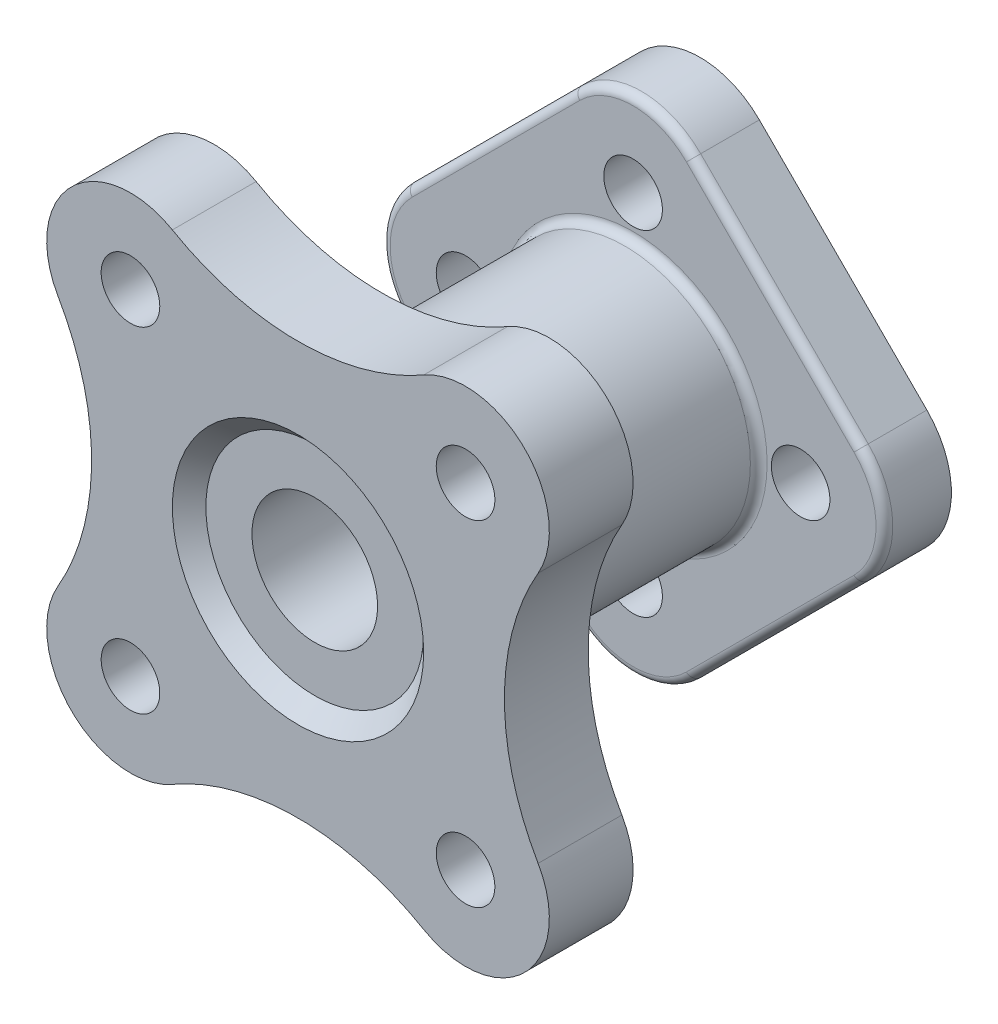
SolidWorks part; units mm, degrees
ref_plane "Front Plane" through (0, 0, 0) normal (0, 0, 1) x (1, 0, 0)
ref_plane "Top Plane" through (0, 0, 0) normal (0, 1, 0) x (1, 0, 0)
ref_plane "Right Plane" through (0, 0, 0) normal (1, 0, 0) x (0, 0, -1)
sketch "Sketch1" plane through (0, 0, 0) normal (0, 0, 1) x (1, 0, 0)
  line L0 (0, 0) -> (0, 1.2321) construction
  line L1 (-1.2321, 0) -> (1.2321, 0) construction
  arc A1 (0.75, 1.433) -> (-0.75, 1.433) centre (0, 2.7321) cw
  arc A2 (0.75, 1.433) -> (1.433, 0.75) centre (1, 1) cw
  arc A3 (1.433, 0.75) -> (1.433, -0.75) centre (2.7321, 0) ccw
  arc A4 (-1.433, 0.75) -> (-1.433, -0.75) centre (-2.7321, 0) cw
  arc A5 (-0.75, 1.433) -> (-1.433, 0.75) centre (-1, 1) ccw
  arc A6 (0.75, -1.433) -> (1.433, -0.75) centre (1, -1) ccw
  arc A7 (0.75, -1.433) -> (-0.75, -1.433) centre (0, -2.7321) ccw
  arc A8 (-0.75, -1.433) -> (-1.433, -0.75) centre (-1, -1) cw
  circle A9 centre (-1, 1) radius 0.175
  circle A10 centre (1, 1) radius 0.175
  circle A11 centre (-1, -1) radius 0.175
  circle A12 centre (1, -1) radius 0.175
  dimension "D1" = 1.5
  dimension "D2" = 0.5
  dimension "D5" = 0.35
  dimension "D3" = 2
  dimension "D4" = 2
extrude "Boss-Extrude1" add sketch "Sketch1" along normal blind 0.5
sketch "Sketch2" plane through (0, 0, 0.5) normal (0, 0, 1) x (1, 0, 0)
  circle A0 centre (0, 0) radius 0.75
  dimension "D1" = 1.5
extrude "Cut-Extrude1" cut sketch "Sketch2" against normal blind 0.1 draft 45
sketch "Sketch3" plane through (0, 0, 0) normal (0, 0, -1) x (-1, 0, 0)
  circle A0 centre (0, 0) radius 0.75 construction
  circle A1 centre (0, 0) radius 0.75
extrude "Boss-Extrude2" add sketch "Sketch3" along normal blind 1.5
sketch "Sketch4" plane through (0, 0, -1.5) normal (0, 0, -1) x (-1, 0, 0)
  line L0 (-0.3536, -1.3536) -> (-1.3536, -0.3536)
  line L1 (0.3536, -1.3536) -> (1.3536, -0.3536)
  line L2 (-1.3536, 0.3536) -> (-0.3536, 1.3536)
  line L3 (1.3536, 0.3536) -> (0.3536, 1.3536)
  arc A0 (-1.3536, -0.3536) -> (-1.3536, 0.3536) centre (-1, 0) cw
  arc A1 (-0.3536, -1.3536) -> (0.3536, -1.3536) centre (0, -1) ccw
  arc A2 (1.3536, 0.3536) -> (1.3536, -0.3536) centre (1, 0) cw
  arc A3 (0.3536, 1.3536) -> (-0.3536, 1.3536) centre (0, 1) ccw
  circle A4 centre (-1, 0) radius 0.175
  circle A5 centre (0, 1) radius 0.175
  circle A6 centre (1, 0) radius 0.175
  circle A7 centre (0, -1) radius 0.175
  point P8 (-1.7071, 0)
  point P11 (0, -1.7071)
  point P14 (1.7071, 0)
  point P17 (0, 1.7071)
  point P18 (0, 0)
  point P27 (0, 0)
  dimension "D1" = 0.5
  dimension "D3" = 0.35
  dimension "D2" = 2
  dimension "D5" = 2
  dimension "D4" = 4
extrude "Boss-Extrude3" add sketch "Sketch4" along normal blind 0.4
sketch "Sketch5" plane through (0, 0, 0.4) normal (0, 0, 1) x (1, 0, 0)
  circle A0 centre (0, 0) radius 0.375
  dimension "D1" = 0.75
extrude "Cut-Extrude2" cut sketch "Sketch5" against normal through all
fillet "Fillet1" radius 0.05 9 edges at (0, 1.5, -1.5) (-0.8536, 0.8536, -1.5) (-1.5, 0, -1.5) (-0.8536, -0.8536, -1.5) (0, -1.5, -1.5) (0.8536, -0.8536, -1.5) (1.5, 0, -1.5) (0.8536, 0.8536, -1.5) (-0.75, 0, -1.5)
